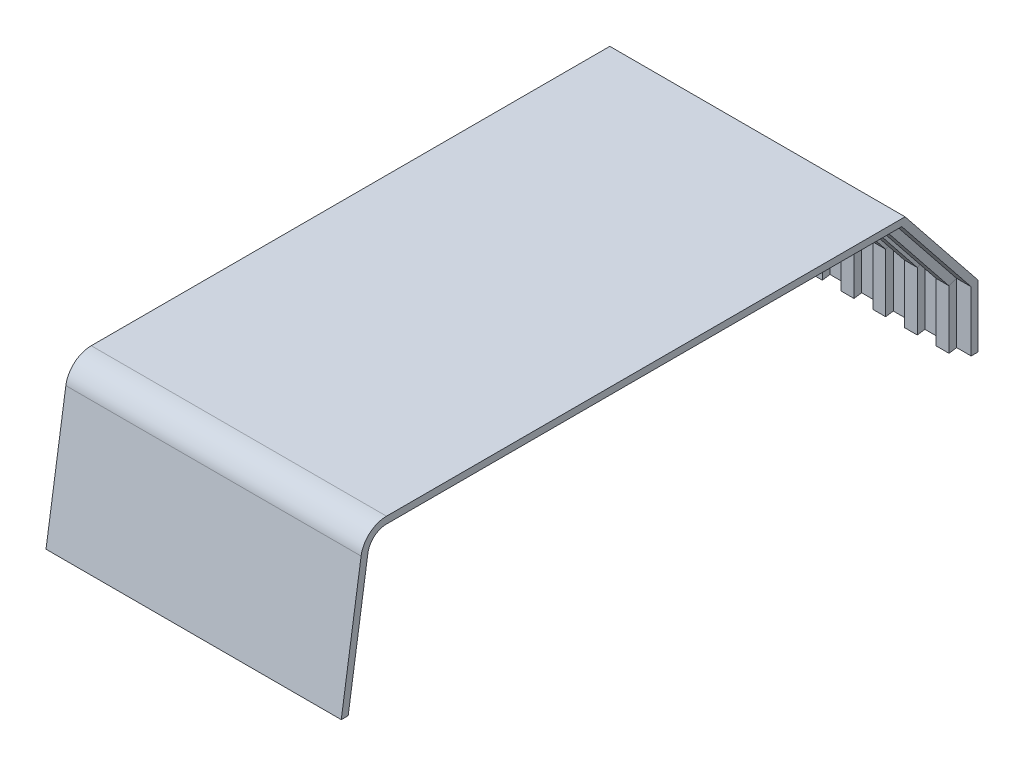
SolidWorks part; units mm, degrees
ref_plane "前视基准面" through (0, 0, 0) normal (0, 0, 1) x (1, 0, 0)
ref_plane "上视基准面" through (0, 0, 0) normal (0, 1, 0) x (1, 0, 0)
ref_plane "右视基准面" through (0, 0, 0) normal (1, 0, 0) x (0, 0, -1)
sketch "草图2" plane through (0, 0, 0) normal (1, 0, 0) x (0, 0, -1)
  line L32 (-2.0016, 3.1471) -> (-2.0016, 17.1644)
  line L33 (-2.0016, 17.1644) -> (-18.214, 37.4471)
  line L34 (-18.214, 37.4471) -> (-138.6289, 37.4471)
  line L35 (-142.9799, 33.7021) -> (-147.58, 3.1471)
  line L37 (-2.0016, 3.1471) -> (-0.4016, 3.1471)
  line L38 (-17.4446, 39.0471) -> (-138.6289, 39.0471)
  line L39 (-144.5621, 33.9403) -> (-149.198, 3.1471)
  line L40 (-0.4016, 3.1471) -> (-0.4016, 17.7253)
  line L41 (-0.4016, 17.7253) -> (-17.4446, 39.0471)
  line L42 (-147.58, 3.1471) -> (-149.198, 3.1471)
  line L43 (-142.9799, 33.7021) -> (-147.9563, 0.6471) construction
  line L44 (-147.9563, 0.6471) -> (-2.0016, 0.6471) construction
  line L45 (-149.8153, -0.9529) -> (-0.4016, -0.9529) construction
  line L46 (-144.5621, 33.9403) -> (-149.8153, -0.9529) construction
  line L47 (-0.4016, -0.9529) -> (-0.4016, 17.7253) construction
  line L48 (-2.0016, 0.6471) -> (-2.0016, 17.1644) construction
  arc A4 (-138.6289, 39.0471) -> (-144.5621, 33.9403) centre (-138.6289, 33.0471) ccw
  arc A5 (-138.6289, 37.4471) -> (-142.9799, 33.7021) centre (-138.6289, 33.0471) ccw
  dimension "D1" = 1.6
  dimension "D3" = 6
extrude "凸台-拉伸1" add sketch "草图2" along normal blind 69
sketch "草图7" plane through (0, 3.1471, 0) normal (0, -1, 0) x (1, 0, 0)
  line L1 (33, 147.58) -> (33, 145.78)
  line L2 (33, 145.78) -> (36, 145.78)
  line L3 (36, 145.78) -> (36, 147.58)
  line L28 (28.6, 145.78) -> (28.6, 147.58)
  line L29 (25.6, 145.78) -> (28.6, 145.78)
  line L30 (25.6, 147.58) -> (25.6, 145.78)
  line L31 (21.2, 145.78) -> (21.2, 147.58)
  line L32 (18.2, 145.78) -> (21.2, 145.78)
  line L33 (18.2, 147.58) -> (18.2, 145.78)
  line L34 (13.8, 145.78) -> (13.8, 147.58)
  line L35 (10.8, 145.78) -> (13.8, 145.78)
  line L36 (10.8, 147.58) -> (10.8, 145.78)
  line L37 (6.4, 145.78) -> (6.4, 147.58)
  line L38 (3.4, 145.78) -> (6.4, 145.78)
  line L39 (3.4, 147.58) -> (3.4, 145.78)
  line L40 (36, 145.78) -> (28.6, 145.78) construction
  line L41 (40.4, 147.58) -> (40.4, 145.78)
  line L42 (43.4, 145.78) -> (43.4, 147.58)
  line L43 (43.4, 147.58) -> (40.4, 147.58)
  line L44 (40.4, 145.78) -> (43.4, 145.78)
  line L45 (47.8, 147.58) -> (47.8, 145.78)
  line L46 (50.8, 145.78) -> (50.8, 147.58)
  line L47 (50.8, 147.58) -> (47.8, 147.58)
  line L48 (47.8, 145.78) -> (50.8, 145.78)
  line L49 (55.2, 147.58) -> (55.2, 145.78)
  line L50 (58.2, 145.78) -> (58.2, 147.58)
  line L51 (58.2, 147.58) -> (55.2, 147.58)
  line L52 (55.2, 145.78) -> (58.2, 145.78)
  line L53 (62.6, 147.58) -> (62.6, 145.78)
  line L54 (65.6, 145.78) -> (65.6, 147.58)
  line L55 (65.6, 147.58) -> (62.6, 147.58)
  line L56 (62.6, 145.78) -> (65.6, 145.78)
  line L57 (33, 147.58) -> (40.4, 147.58) construction
  line L103 (28.6, 147.58) -> (25.6, 147.58)
  line L104 (21.2, 147.58) -> (18.2, 147.58)
  line L105 (13.8, 147.58) -> (10.8, 147.58)
  line L106 (36, 147.58) -> (33, 147.58)
  line L107 (6.4, 147.58) -> (3.4, 147.58)
  dimension "D1" = 3
  dimension "D2" = 33
  dimension "D5" = 7.4
  dimension "D7" = 7.4
  dimension "D3" = 5
  dimension "D4" = 1
  dimension "D6" = 5
sketch "草图17" plane through (0, 0, 0) normal (-1, 0, 0) x (0, 0, 1)
  line L0 (147.58, 3.1471) -> (143.0568, 33.1914)
  line L1 (147.58, 3.1471) -> (142.9799, 33.7021) construction
  line L2 (138.1125, 37.4471) -> (18.214, 37.4471)
  line L3 (138.6289, 37.4471) -> (18.214, 37.4471) construction
  line L5 (18.214, 37.4471) -> (2.0016, 17.1644)
  line L6 (2.0016, 17.1644) -> (2.0016, 3.1471)
  arc A0 (138.1125, 37.4471) -> (143.0568, 33.1914) centre (138.1125, 32.4471) cw
  dimension "D1" = 5
sweep "扫描1" add profiles "草图7" path "草图17"
